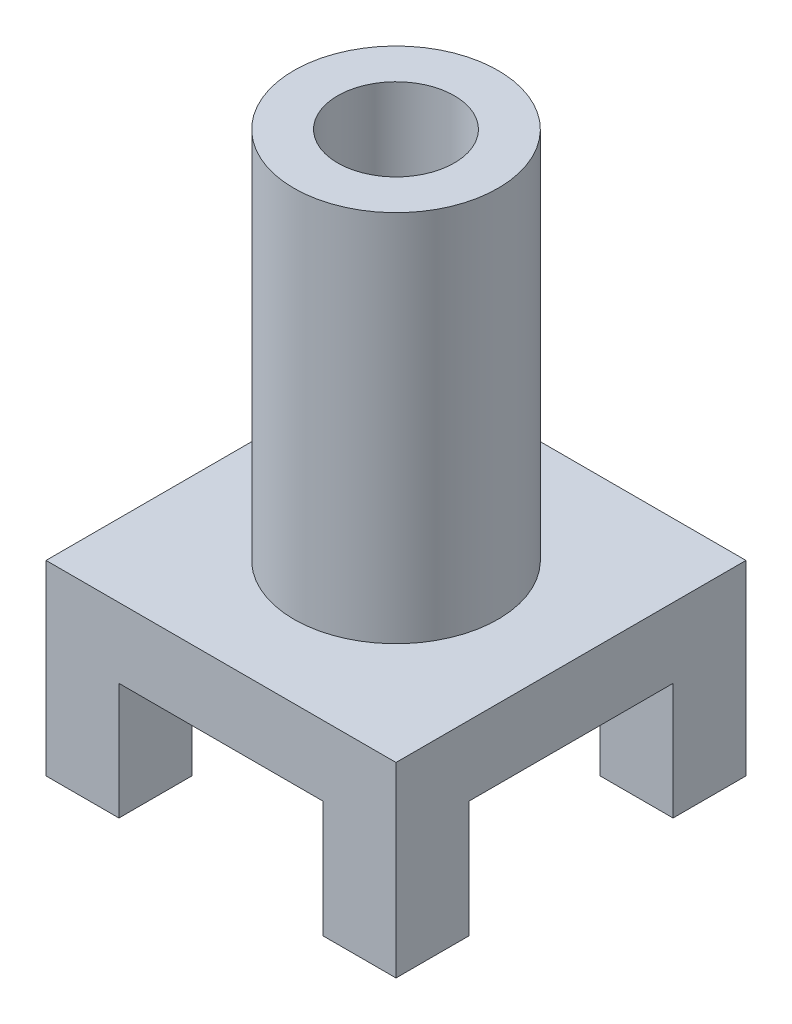
SolidWorks part; units mm, degrees
ref_plane "Alzado" through (0, 0, 0) normal (0, 0, 1) x (1, 0, 0)
ref_plane "Planta" through (0, 0, 0) normal (0, 1, 0) x (1, 0, 0)
ref_plane "Vista lateral" through (0, 0, 0) normal (1, 0, 0) x (0, 0, -1)
sketch "Croquis1" plane through (0, 0, 0) normal (0, 1, 0) x (1, 0, 0)
  line L1 (-30, 30) -> (30, 30)
  line L2 (-30, 30) -> (-30, -30)
  line L3 (-30, -30) -> (30, -30)
  line L4 (30, 30) -> (30, -30)
  line L5 (-30, 30) -> (30, -30) construction
  line L6 (-30, -30) -> (30, 30) construction
  point P0 (0, 0)
  dimension "D1" = 60
  dimension "D2" = 60
extrude "Saliente-Extruir2" add sketch "Croquis1" along normal blind 32 contours L2 L1 L4 L3
sketch "Croquis2" plane through (30, 0, 0) normal (1, 0, 0) x (0, 0, -1)
  line L0 (30, 0) -> (-30, 0) construction
  line L1 (-17.5, 0) -> (17.5, 0)
  line L2 (-17.5, 0) -> (-17.5, 20)
  line L3 (-17.5, 20) -> (17.5, 20)
  line L4 (17.5, 0) -> (17.5, 20)
  dimension "D1" = 20
  dimension "D2" = 35
  dimension "D3" = 17.5
extrude "Cortar-Extruir1" cut sketch "Croquis2" against normal through all
sketch "Croquis4" plane through (0, 0, 30) normal (0, 0, 1) x (1, 0, 0)
  line L0 (-30, 0) -> (30, 0) construction
  line L1 (-17.5, 0) -> (17.5, 0)
  line L2 (-17.5, 0) -> (-17.5, 20)
  line L3 (-17.5, 20) -> (17.5, 20)
  line L4 (17.5, 0) -> (17.5, 20)
  dimension "D1" = 20
  dimension "D2" = 35
  dimension "D3" = 17.5
extrude "Cortar-Extruir3" cut sketch "Croquis4" against normal through all contours L2 L1 L4 L3
sketch "Croquis5" plane through (0, 32, 0) normal (0, 1, 0) x (1, 0, 0)
  circle A0 centre (0, 0) radius 17.5
  dimension "D1" = 35
extrude "Saliente-Extruir3" add sketch "Croquis5" along normal blind 64
sketch "Croquis6" plane through (0, 96, 0) normal (0, 1, 0) x (1, 0, 0)
  circle A0 centre (0, 0) radius 10
  dimension "D1" = 20
extrude "Cortar-Extruir5" cut sketch "Croquis6" against normal through all
